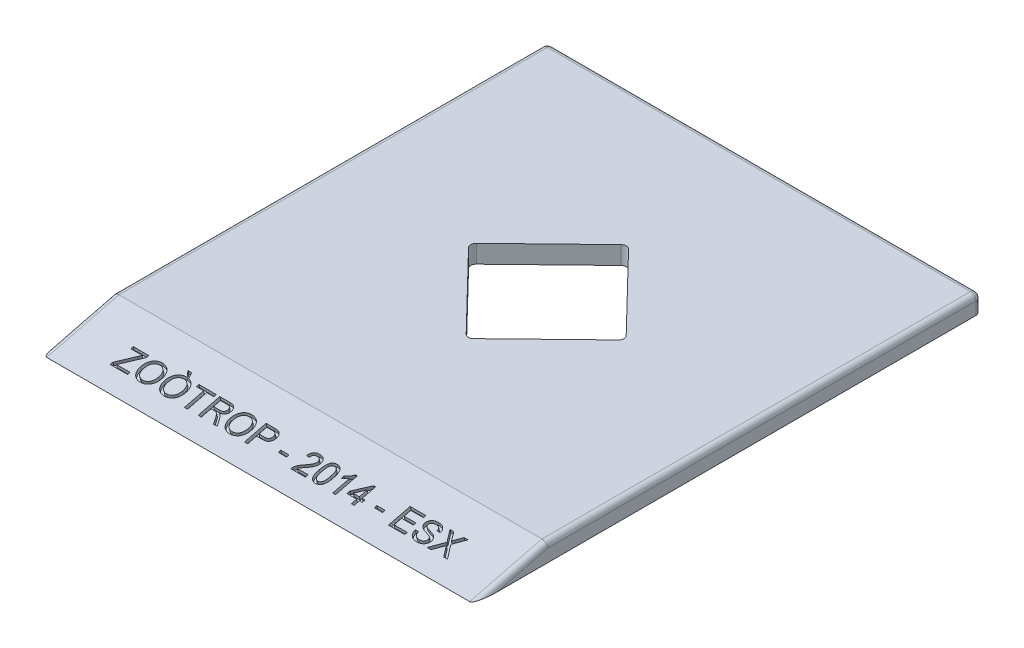
SolidWorks part; units mm, degrees
ref_plane "Alzado" through (0, 0, 0) normal (0, 0, 1) x (1, 0, 0)
ref_plane "Planta" through (0, 0, 0) normal (0, 1, 0) x (1, 0, 0)
ref_plane "Vista lateral" through (0, 0, 0) normal (1, 0, 0) x (0, 0, -1)
sketch "Croquis1" plane through (0, 0, 0) normal (0, 1, 0) x (1, 0, 0)
  line L1 (-60, 60) -> (60, 60) construction
  line L2 (-60, 60) -> (-60, -80) construction
  line L3 (-60, -80) -> (60, -80) construction
  line L4 (60, 60) -> (60, -80) construction
  circle A0 centre (0, 0) radius 50 construction
  dimension "D1" = 100
  dimension "D2" = 60
  dimension "D3" = 60
  dimension "D4" = 140
  dimension "D5" = 120
sketch "Croquis2" plane through (0, 0, 0) normal (1, 0, 0) x (0, 0, -1)
  line L0 (60, 0) -> (-80, 0)
  line L3 (-80, 0) -> (-60, 5)
  line L4 (-60, 5) -> (60, 5)
  line L5 (60, 5) -> (60, 0)
  dimension "D1" = 120
  dimension "D2" = 60
  dimension "D3" = 5
  dimension "D4" = 140
extrude "Saliente-Extruir1" add sketch "Croquis2" along normal mid plane 120
sketch "Croquis3" plane through (0, 18.8235, 4.7059) normal (0, 0.9701, 0.2425) x (1, 0, 0)
  line L0 (-60, -71.7649) -> (60, -71.7649) construction
  line L1 (-60, 58.2086) -> (-60, -77.6114) construction
  line L2 (60, 58.2086) -> (60, -77.6114) construction
  text T0 "ZOÒTROP - 2014 - ESX" font "Arial" height in points 24
extrude "Cortar-Extruir1" cut sketch "Croquis3" against normal blind 1
sketch "Croquis4" plane through (0, 5, 0) normal (0, 1, 0) x (1, 0, 0)
  line L0 (0, 22.4888) -> (-22.4777, 0.707)
  line L1 (0, 22.4888) -> (22.4777, -0.707)
  line L2 (-22.4777, 0.707) -> (0, -22.4888)
  line L3 (22.4777, -0.707) -> (0, -22.4888)
  line L4 (-22.4777, 0.707) -> (22.4777, -0.707) construction
  line L5 (0, 22.4888) -> (0, -22.4888) construction
  dimension "D1" = 31.3
  dimension "D2" = 32.3
extrude "Cortar-Extruir2" cut sketch "Croquis4" against normal blind 21
fillet "Redondeo1" radius 1.5 4 edges at (0, 2.5, 22.4888) (22.4777, 2.5, 0.707) (-22.4777, 2.5, -0.707) (0, 2.5, -22.4888)
fillet "Redondeo2" radius 1.5 7 edges at (0, 5, -60) (60, 5, 0) (60, 2.5, 70) (-60, 2.5, 70) (-60, 5, 0) (-60, 2.5, -60) (60, 2.5, -60)
